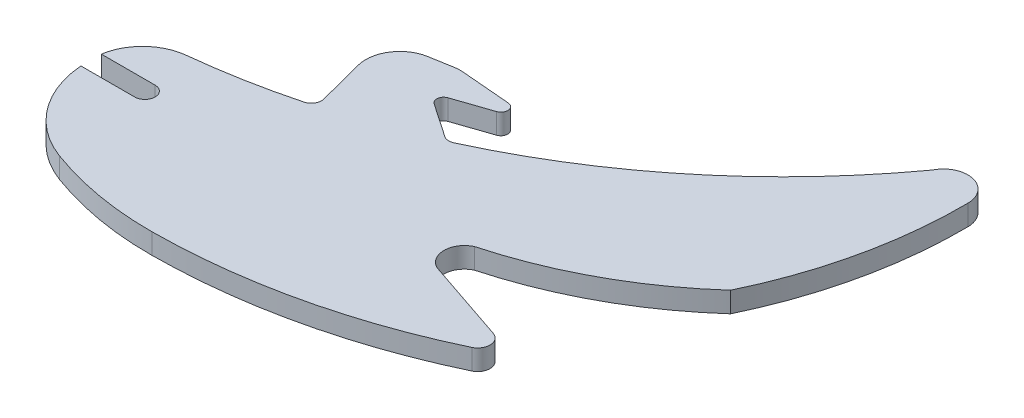
SolidWorks part; units mm, degrees
ref_plane "Front Plane" through (0, 0, 0) normal (0, 0, 1) x (1, 0, 0)
ref_plane "Top Plane" through (0, 0, 0) normal (0, 1, 0) x (1, 0, 0)
ref_plane "Right Plane" through (0, 0, 0) normal (1, 0, 0) x (0, 0, -1)
sketch "Sketch1" plane through (0, 0, 0) normal (0, 1, 0) x (1, 0, 0)
  line L0 (0, 0) -> (7.87, 0)
  line L1 (7.87, 3) -> (0, 3)
  line L2 (51.7065, 0.4691) -> (64.1049, -3.7205)
  line L3 (18.83, 25.66) -> (22.36, 12.1469)
  line L5 (18.83, 25.66) -> (28.1065, 27.26)
  line L6 (40.7436, 26.19) -> (29.01, 22.19)
  line L7 (29.01, 22.19) -> (36.3, 17.2075)
  line L8 (28.1065, 27.26) -> (40.7436, 26.19)
  arc A0 (7.87, 0) -> (7.87, 3) centre (7.87, 1.5) ccw
  arc A1 (75.5063, 49.1) -> (36.3, 17.2075) centre (-4.2, 107.04) cw
  arc A2 (6.36, 9.0675) -> (0, 3) centre (7.1337, 1.8894) ccw
  arc A3 (75.5063, 49.1) -> (82.3363, 47.5681) centre (78.7414, 47.5321) cw
  arc A4 (82.3363, 47.5681) -> (76, 19.13) centre (18.2287, 46.9269) cw
  arc A5 (51.7065, 5.9109) -> (51.7065, 0.4691) centre (52.97, 3.19) ccw
  arc A7 (64.1049, -3.7205) -> (64.3035, -7.0704) centre (63.5253, -5.4357) cw
  arc A8 (64.3035, -7.0704) -> (26.1998, -15.8204) centre (25.5593, 74.3098) cw
  arc A9 (9.7962, -12.9525) -> (0, 0) centre (15.0023, 1.1657) cw
  arc A10 (9.7962, -12.9525) -> (26.1998, -15.8204) centre (25.8696, 30.6368) ccw
  arc A11 (51.7065, 5.9109) -> (76, 19.13) centre (36.0062, 63.6968) ccw
  arc A12 (22.36, 12.1469) -> (6.36, 9.0675) centre (-4.2, 107.04) cw
  point P5 (9.37, 1.5)
  point P7 (27.07, -15.81)
  point P8 (-4.2, 107.04)
  point P18 (79.5282, 51.04)
  point P21 (49.97, 3.19)
  dimension "D1" = 1.5
  dimension "D7" = 98.54
  dimension "D13" = 64.1108
  dimension "D14" = 3.595
  dimension "D16" = 3
  dimension "D19" = 1.8105
  dimension "D21" = 90.1325
  dimension "D22" = 46.4583
  dimension "D33" = 15.0475
  dimension "D34" = 59.8807
  dimension "D2" = 9.37
  dimension "D3" = 27.07
  dimension "D4" = 15.81
  dimension "D5" = 104.04
  dimension "D6" = 4.2
  dimension "D8" = 6.36
  dimension "D9" = 64.91
  dimension "D10" = 34.94
  dimension "D11" = 66.85
  dimension "D12" = 76
  dimension "D15" = 40.6
  dimension "D17" = 19
  dimension "D18" = 10.3846
  dimension "D20" = 36.4553
  dimension "D23" = 41.47
  dimension "D24" = 29.01
  dimension "D25" = 18.83
  dimension "D26" = 22.36
  dimension "D27" = 38
  dimension "D28" = 13.94
  dimension "D29" = 21.92
  dimension "D30" = 42
  dimension "D31" = 1.6
  dimension "D32" = 9.2765
  dimension "D35" = 9.7962
  dimension "D36" = 36.0062
extrude "Boss-Extrude1" add sketch "Sketch1" along normal blind 3
fillet "Fillet1" radius 5 2 edges at (18.83, 1.5, -25.66) (28.1065, 1.5, -27.26)
fillet "Fillet2" radius 1 2 edges at (29.01, 1.5, -22.19) (40.7436, 1.5, -26.19)
fillet "Fillet3" radius 1.5 2 edges at (36.3, 1.5, -17.2075) (22.36, 1.5, -12.1469)
